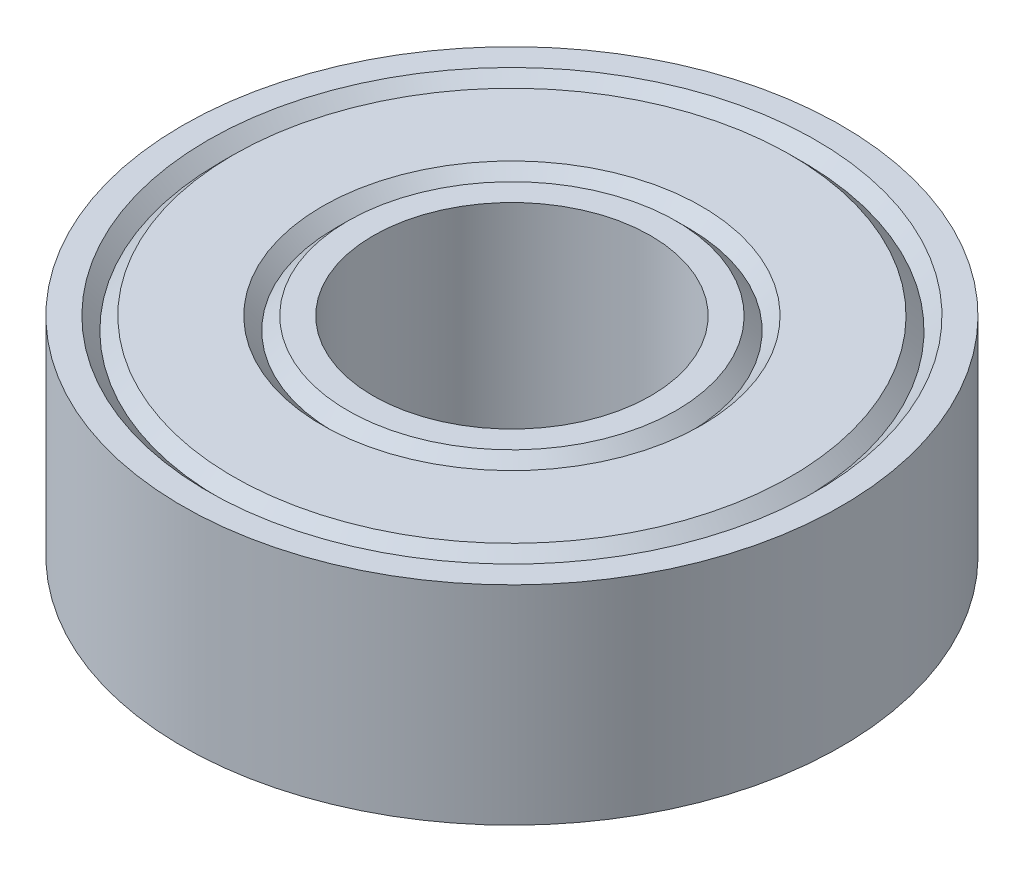
SolidWorks part; units mm, degrees
ref_plane "Front Plane" through (0, 0, 0) normal (0, 0, 1) x (1, 0, 0)
ref_plane "Top Plane" through (0, 0, 0) normal (0, 1, 0) x (1, 0, 0)
ref_plane "Right Plane" through (0, 0, 0) normal (1, 0, 0) x (0, 0, -1)
sketch "Sketch1" plane through (0, 0, 0) normal (0, 0, 1) x (1, 0, 0)
  line L0 (0, 3) -> (0, -3) construction
  line L1 (-4, 3) -> (-4.7333, 3)
  line L2 (-4, 3) -> (-4, -3)
  line L3 (-4, -3) -> (-4.7333, -3)
  line L4 (-9.5, 3) -> (-9.5, -3)
  line L5 (-8.7667, 3) -> (-8.4, 2.6333)
  line L6 (-8.4, 2.6333) -> (-8.0333, 3)
  line L7 (-5.4667, 3) -> (-5.1, 2.6333)
  line L8 (-5.1, 2.6333) -> (-4.7333, 3)
  line L9 (-8.7667, -3) -> (-8.4, -2.6333)
  line L10 (-8.4, -2.6333) -> (-8.0333, -3)
  line L11 (-5.4667, -3) -> (-5.1, -2.6333)
  line L12 (-5.1, -2.6333) -> (-4.7333, -3)
  line L13 (-5.4667, -3) -> (-8.0333, -3)
  line L14 (-8.7667, -3) -> (-9.5, -3)
  line L15 (-8.7667, 3) -> (-9.5, 3)
  line L16 (-5.4667, 3) -> (-8.0333, 3)
  line L17 (-8.4, 2.6333) -> (-5.1, 2.6333) construction
  line L18 (-8.4, 2.6333) -> (-8.4, -2.6333) construction
  line L19 (-5.1, -2.6333) -> (-8.4, -2.6333) construction
  line L20 (-5.1, 2.6333) -> (-5.1, -2.6333) construction
  line L21 (-8.4, 0) -> (-7.3, 0) construction
  line L22 (-4.7333, 3) -> (-5.4667, 3) construction
  line L23 (-7.3, 0) -> (-6.2, 0) construction
  line L24 (-8.4, 0) -> (-9.5, 0) construction
  line L25 (-6.2, 0) -> (-5.1, 0) construction
  line L26 (-5.1, 0) -> (-4, 0) construction
  dimension "D1" = 6
  dimension "D2" = 8
  dimension "D3" = 19
revolve "Revolve1" add sketch "Sketch1" angle 360 about L0
